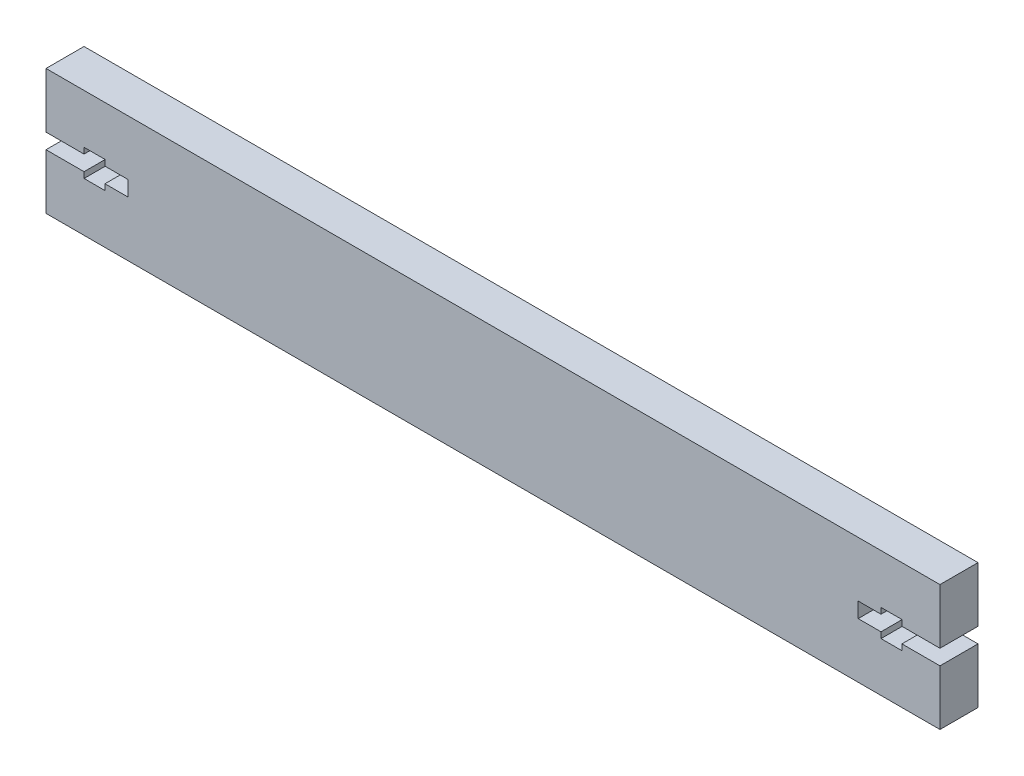
SolidWorks part; units mm, degrees
ref_plane "Plan de face" through (0, 0, 0) normal (0, 0, 1) x (1, 0, 0)
ref_plane "Plan de dessus" through (0, 0, 0) normal (0, 1, 0) x (1, 0, 0)
ref_plane "Plan de droite" through (0, 0, 0) normal (1, 0, 0) x (0, 0, -1)
sketch "Esquisse1" plane through (0, 0, 0) normal (0, 0, 1) x (1, 0, 0)
  line L1 (-117.5, 16.5) -> (117.5, 16.5)
  line L2 (-117.5, 16.5) -> (-117.5, -16.5)
  line L3 (-117.5, -16.5) -> (117.5, -16.5)
  line L4 (117.5, 16.5) -> (117.5, -16.5)
  line L5 (-117.5, 16.5) -> (117.5, -16.5) construction
  line L6 (-117.5, -16.5) -> (117.5, 16.5) construction
  point P0 (0, 0)
  dimension "D1" = 33
  dimension "D2" = 235
extrude "Boss.-Extru.1" add sketch "Esquisse1" along normal blind 10
sketch "Esquisse2" plane through (0, 0, 10) normal (0, 0, 1) x (1, 0, 0)
  line L0 (-117.5, 2) -> (-107.5, 2)
  line L1 (-117.5, 16.5) -> (-117.5, -16.5) construction
  line L2 (-107.5, 2) -> (-107.5, 3.55)
  line L3 (-107.5, 3.55) -> (-102, 3.55)
  line L4 (-102, 3.55) -> (-102, 2)
  line L5 (-102, 2) -> (-96, 2)
  line L6 (-96, 2) -> (-96, -2)
  line L7 (-117.5, 2) -> (-117.5, -2)
  line L8 (-117.5, 0) -> (-96, 0) construction
  line L9 (-102, -2) -> (-96, -2)
  line L10 (-102, -3.55) -> (-102, -2)
  line L11 (-107.5, -3.55) -> (-102, -3.55)
  line L12 (-107.5, -2) -> (-107.5, -3.55)
  line L13 (-117.5, -2) -> (-107.5, -2)
  line L14 (117.5, 16.5) -> (-117.5, 16.5) construction
  line L15 (0, 16.5) -> (0, -16.5) construction
  line L16 (-117.5, -16.5) -> (117.5, -16.5) construction
  line L17 (117.5, 0) -> (96, 0) construction
  line L18 (117.5, -2) -> (107.5, -2)
  line L19 (107.5, -2) -> (107.5, -3.55)
  line L20 (107.5, -3.55) -> (102, -3.55)
  line L21 (102, -3.55) -> (102, -2)
  line L22 (102, -2) -> (96, -2)
  line L23 (117.5, 2) -> (117.5, -2)
  line L24 (96, 2) -> (96, -2)
  line L25 (102, 2) -> (96, 2)
  line L26 (102, 3.55) -> (102, 2)
  line L27 (107.5, 3.55) -> (102, 3.55)
  line L28 (107.5, 2) -> (107.5, 3.55)
  line L29 (117.5, 2) -> (107.5, 2)
  dimension "D1" = 5.5
  dimension "D2" = 10
  dimension "D3" = 6
  dimension "D4" = 2
  dimension "D5" = 2
  dimension "D6" = 7.1
  dimension "D7" = 16.5
extrude "Enlèv. mat.-Extru.1" cut sketch "Esquisse2" against normal blind 10
